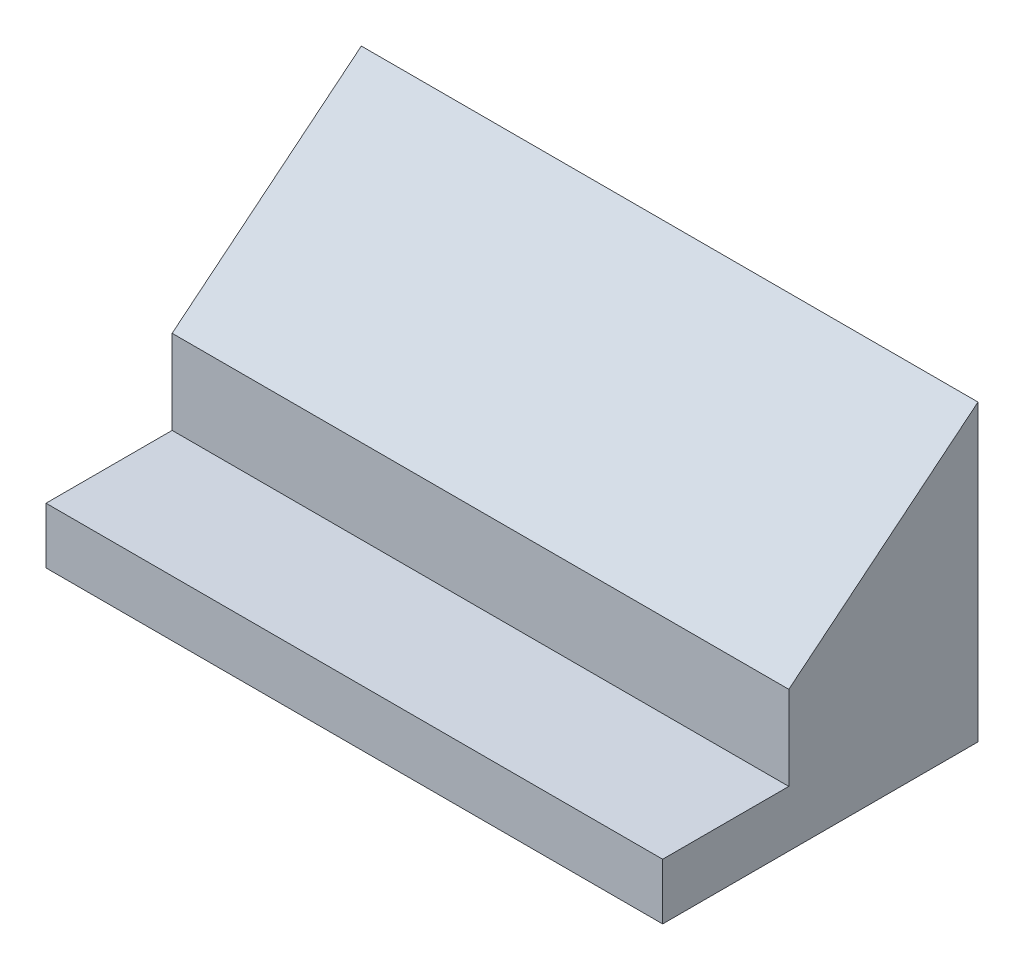
SolidWorks part; units mm, degrees
ref_plane "Front Plane" through (0, 0, 0) normal (0, 0, 1) x (1, 0, 0)
ref_plane "Top Plane" through (0, 0, 0) normal (0, 1, 0) x (1, 0, 0)
ref_plane "Right Plane" through (0, 0, 0) normal (1, 0, 0) x (0, 0, -1)
sketch "Sketch2" plane through (0, 0, 0) normal (1, 0, 0) x (0, 0, -1)
  line L0 (0, 0) -> (4.5, 0)
  line L1 (4.5, 0) -> (4.5, 4.2)
  line L2 (0, 0) -> (0, 0.8)
  line L3 (0, 0.8) -> (1.8, 0.8)
  line L4 (1.8, 0.8) -> (1.8, 2)
  line L5 (1.8, 2) -> (4.5, 4.2)
  dimension "D1" = 0.8
  dimension "D2" = 1.8
  dimension "D3" = 4.5
  dimension "D4" = 4.2
  dimension "D5" = 1.2
extrude "Boss-Extrude1" add sketch "Sketch2" along normal blind 8.8
